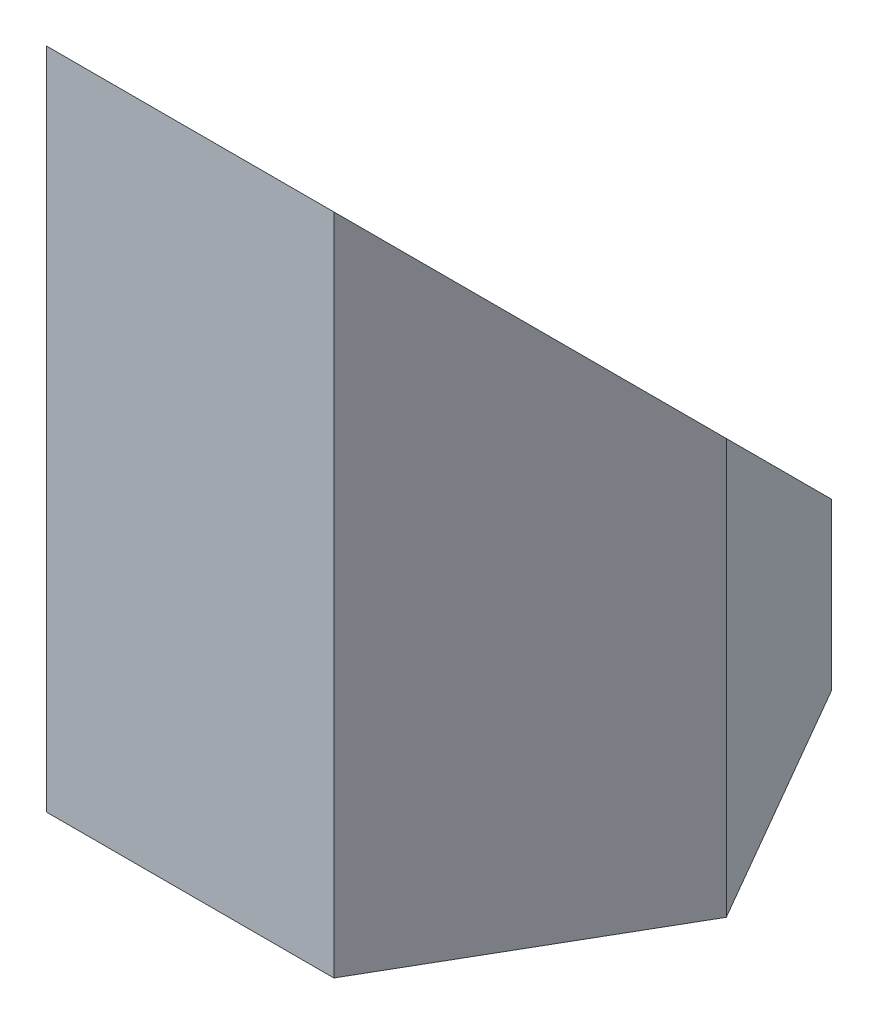
SolidWorks part; units mm, degrees
ref_plane "Front Plane" through (0, 0, 0) normal (0, 0, 1) x (1, 0, 0)
ref_plane "Top Plane" through (0, 0, 0) normal (0, 1, 0) x (1, 0, 0)
ref_plane "Right Plane" through (0, 0, 0) normal (1, 0, 0) x (0, 0, -1)
sketch3d "3DSketch1"
  point P5 (0, 0, 0)
  point P8 (-8.6603, 0, 15)
  point P9 (-8.6603, 0, 15)
  point P11 (17.3205, 0, 30)
sketch "Sketch13" plane through (0, 0, 0) normal (0, 1, 0) x (1, 0, 0)
  line L7 (-69.282, 0) -> (0, 0)
  line L8 (-69.282, 0) -> (-69.282, -60)
  line L9 (-69.282, -60) -> (0, -60)
  line L10 (0, 0) -> (0, -60)
  point P0 (0, 0)
  dimension "D2" = 69.282
  dimension "D3" = 60
extrude "Boss-Extrude3" add sketch "Sketch13" along normal blind 80
sketch "Sketch14" plane through (0, 0, 0) normal (1, 0, 0) x (0, 0, -1)
  line L0 (-60, 80) -> (0, 20)
  line L1 (0, 80) -> (0, 0) construction
  line L2 (0, 20) -> (0, 80)
  line L3 (0, 80) -> (-60, 80)
  dimension "D1" = 45
extrude "Cut-Extrude5" cut sketch "Sketch14" against normal blind 80
sketch "Sketch15" plane through (0, 0, 0) normal (0, -1, 0) x (-1, 0, 0)
  line L0 (51.9615, -60) -> (69.282, -60)
  line L1 (0, -30) -> (17.3205, -60)
  line L2 (17.3205, -60) -> (51.9615, -60)
  line L3 (51.9615, -60) -> (69.282, -30)
  line L4 (69.282, -30) -> (51.9615, 0)
  line L5 (51.9615, 0) -> (17.3205, 0)
  line L6 (17.3205, 0) -> (0, -30)
  line L7 (0, -60) -> (0, 0) construction
  line L8 (69.282, -60) -> (0, -60) construction
  line L9 (69.282, -60) -> (69.282, -30)
  line L10 (51.9615, -60) -> (69.282, -60)
  line L11 (69.282, -30) -> (69.282, 0)
  line L12 (69.282, 0) -> (51.9615, 0)
  line L13 (69.282, -60) -> (69.282, -30)
  line L14 (69.282, -60) -> (51.9615, -60)
  line L15 (69.282, -30) -> (51.9615, -60)
  line L16 (17.3205, -60) -> (0, -60)
  line L17 (0, -60) -> (0, -30)
  line L18 (0, -30) -> (17.3205, 0)
  line L19 (0, 0) -> (0, -30)
  circle A0 centre (34.641, -30) radius 30 construction
  circle A1 centre (34.641, -30) radius 12
  point P21 (0, 0)
  point P23 (0, 0)
  point P24 (0, 0)
  line M11 (69.282, -60) -> (69.282, 0)
  line M12 (69.282, 0) -> (0, 0)
  line M13 (0, 0) -> (0, -60)
  line M14 (0, -60) -> (69.282, -60)
  dimension "D2" = 24
  dimension "D1" = 60
extrude "Cut-Extrude6" cut sketch "Sketch15" against normal blind 80 contours L3 M14 M11 | L4 M11 M12 | L1 M13 M14 | L6 M12 M13 | A1
